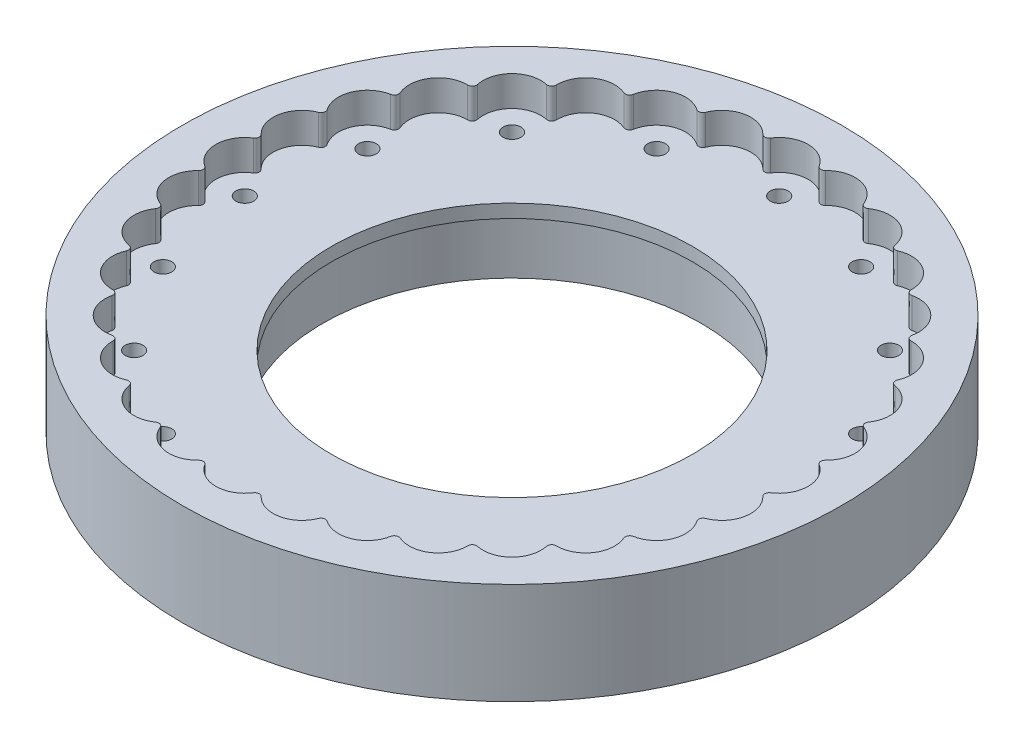
SolidWorks part; units mm, degrees
material "尼龙 101"
ref_plane "前视基准面" through (0, 0, 0) normal (0, 0, 1) x (1, 0, 0)
ref_plane "上视基准面" through (0, 0, 0) normal (0, 1, 0) x (1, 0, 0)
ref_plane "右视基准面" through (0, 0, 0) normal (1, 0, 0) x (0, 0, -1)
sketch "草图1" plane through (0, 0, 0) normal (0, 1, 0) x (1, 0, 0)
  line L0 (-3, 0) -> (-61.8471, 11.7054) construction
  line L1 (-63, 0) -> (-3, 0) construction
  line L2 (-3, 0) -> (-62.7111, 5.881) construction
  line L3 (-61.8471, 11.7054) -> (-80.5752, 15.4307) construction
  line L4 (-63, 0) -> (-84.6703, 0) construction
  arc A23 (51.1029, 1.1255) -> (51, 0) centre (57.2058, 0) ccw construction
  circle A26 centre (-45.4264, 42.4264) radius 6.5 construction
  circle A27 centre (-25.961, 55.4328) radius 6.5 construction
  circle A28 centre (-3, 60) radius 6.5 construction
  circle A29 centre (19.961, 55.4328) radius 6.5 construction
  circle A30 centre (39.4264, 42.4264) radius 6.5 construction
  circle A31 centre (52.4328, 22.961) radius 6.5 construction
  circle A32 centre (57, 0) radius 6.5 construction
  circle A33 centre (52.4328, -22.961) radius 6.5 construction
  circle A34 centre (39.4264, -42.4264) radius 6.5 construction
  circle A35 centre (19.961, -55.4328) radius 6.5 construction
  circle A36 centre (-3, -60) radius 6.5 construction
  circle A37 centre (-25.961, -55.4328) radius 6.5 construction
  circle A38 centre (-45.4264, -42.4264) radius 6.5 construction
  circle A39 centre (-58.4328, -22.961) radius 6.5 construction
  circle A40 centre (-3, 0) radius 74
  circle A42 centre (-3, 0) radius 60 construction
  arc A46 (-68.2222, 12.9735) -> (-65.1785, 6.1241) centre (-61.8471, 11.7054) ccw
  arc A48 (-69.5, 0) -> (-65.1785, 6.1241) centre (-63, 0) cw
  arc A49 (-68.2222, 12.9735) -> (-62.789, 18.1368) centre (-61.8471, 11.7054) cw
  arc A50 (-64.438, 25.4484) -> (-62.789, 18.1368) centre (-58.4328, 22.961) ccw
  arc A51 (-64.438, 25.4484) -> (-58.1019, 29.4526) centre (-58.4328, 22.961) cw
  arc A52 (-58.2927, 36.9454) -> (-58.1019, 29.4526) centre (-52.8882, 33.3342) ccw
  arc A53 (-58.2927, 36.9454) -> (-51.2972, 39.6365) centre (-52.8882, 33.3342) cw
  arc A54 (-50.0226, 47.0226) -> (-51.2972, 39.6365) centre (-45.4264, 42.4264) ccw
  arc A55 (-50.0226, 47.0226) -> (-42.6365, 48.2972) centre (-45.4264, 42.4264) cw
  arc A56 (-39.9454, 55.2927) -> (-42.6365, 48.2972) centre (-36.3342, 49.8882) ccw
  arc A57 (-39.9454, 55.2927) -> (-32.4526, 55.1019) centre (-36.3342, 49.8882) cw
  arc A58 (-28.4484, 61.438) -> (-32.4526, 55.1019) centre (-25.961, 55.4328) ccw
  arc A59 (-28.4484, 61.438) -> (-21.1368, 59.789) centre (-25.961, 55.4328) cw
  arc A60 (-15.9735, 65.2222) -> (-21.1368, 59.789) centre (-14.7054, 58.8471) ccw
  arc A61 (-15.9735, 65.2222) -> (-9.1241, 62.1785) centre (-14.7054, 58.8471) cw
  arc A62 (-3, 66.5) -> (-9.1241, 62.1785) centre (-3, 60) ccw
  arc A63 (-3, 66.5) -> (3.1241, 62.1785) centre (-3, 60) cw
  arc A64 (9.9735, 65.2222) -> (3.1241, 62.1785) centre (8.7054, 58.8471) ccw
  arc A65 (9.9735, 65.2222) -> (15.1368, 59.789) centre (8.7054, 58.8471) cw
  arc A66 (22.4484, 61.438) -> (15.1368, 59.789) centre (19.961, 55.4328) ccw
  arc A67 (22.4484, 61.438) -> (26.4526, 55.1019) centre (19.961, 55.4328) cw
  arc A68 (33.9454, 55.2927) -> (26.4526, 55.1019) centre (30.3342, 49.8882) ccw
  arc A69 (33.9454, 55.2927) -> (36.6365, 48.2972) centre (30.3342, 49.8882) cw
  arc A70 (44.0226, 47.0226) -> (36.6365, 48.2972) centre (39.4264, 42.4264) ccw
  arc A71 (44.0226, 47.0226) -> (45.2972, 39.6365) centre (39.4264, 42.4264) cw
  arc A72 (52.2927, 36.9454) -> (45.2972, 39.6365) centre (46.8882, 33.3342) ccw
  arc A73 (52.2927, 36.9454) -> (52.1019, 29.4526) centre (46.8882, 33.3342) cw
  arc A74 (58.438, 25.4484) -> (52.1019, 29.4526) centre (52.4328, 22.961) ccw
  arc A75 (58.438, 25.4484) -> (56.789, 18.1368) centre (52.4328, 22.961) cw
  arc A76 (62.2222, 12.9735) -> (56.789, 18.1368) centre (55.8471, 11.7054) ccw
  arc A77 (62.2222, 12.9735) -> (59.1785, 6.1241) centre (55.8471, 11.7054) cw
  arc A78 (63.5, 0) -> (59.1785, 6.1241) centre (57, 0) ccw
  arc A79 (63.5, 0) -> (59.1785, -6.1241) centre (57, 0) cw
  arc A80 (62.2222, -12.9735) -> (59.1785, -6.1241) centre (55.8471, -11.7054) ccw
  arc A81 (62.2222, -12.9735) -> (56.789, -18.1368) centre (55.8471, -11.7054) cw
  arc A82 (58.438, -25.4484) -> (56.789, -18.1368) centre (52.4328, -22.961) ccw
  arc A83 (58.438, -25.4484) -> (52.1019, -29.4526) centre (52.4328, -22.961) cw
  arc A84 (52.2927, -36.9454) -> (52.1019, -29.4526) centre (46.8882, -33.3342) ccw
  arc A85 (52.2927, -36.9454) -> (45.2972, -39.6365) centre (46.8882, -33.3342) cw
  arc A86 (44.0226, -47.0226) -> (45.2972, -39.6365) centre (39.4264, -42.4264) ccw
  arc A87 (44.0226, -47.0226) -> (36.6365, -48.2972) centre (39.4264, -42.4264) cw
  arc A88 (33.9454, -55.2927) -> (36.6365, -48.2972) centre (30.3342, -49.8882) ccw
  arc A89 (33.9454, -55.2927) -> (26.4526, -55.1019) centre (30.3342, -49.8882) cw
  arc A90 (22.4484, -61.438) -> (26.4526, -55.1019) centre (19.961, -55.4328) ccw
  arc A91 (22.4484, -61.438) -> (15.1368, -59.789) centre (19.961, -55.4328) cw
  arc A92 (9.9735, -65.2222) -> (15.1368, -59.789) centre (8.7054, -58.8471) ccw
  arc A93 (9.9735, -65.2222) -> (3.1241, -62.1785) centre (8.7054, -58.8471) cw
  arc A94 (-3, -66.5) -> (3.1241, -62.1785) centre (-3, -60) ccw
  arc A95 (-3, -66.5) -> (-9.1241, -62.1785) centre (-3, -60) cw
  arc A96 (-15.9735, -65.2222) -> (-9.1241, -62.1785) centre (-14.7054, -58.8471) ccw
  arc A97 (-15.9735, -65.2222) -> (-21.1368, -59.789) centre (-14.7054, -58.8471) cw
  arc A98 (-28.4484, -61.438) -> (-21.1368, -59.789) centre (-25.961, -55.4328) ccw
  arc A99 (-28.4484, -61.438) -> (-32.4526, -55.1019) centre (-25.961, -55.4328) cw
  arc A100 (-39.9454, -55.2927) -> (-32.4526, -55.1019) centre (-36.3342, -49.8882) ccw
  arc A101 (-39.9454, -55.2927) -> (-42.6365, -48.2972) centre (-36.3342, -49.8882) cw
  arc A102 (-50.0226, -47.0226) -> (-42.6365, -48.2972) centre (-45.4264, -42.4264) ccw
  arc A103 (-50.0226, -47.0226) -> (-51.2972, -39.6365) centre (-45.4264, -42.4264) cw
  arc A104 (-58.2927, -36.9454) -> (-51.2972, -39.6365) centre (-52.8882, -33.3342) ccw
  arc A105 (-58.2927, -36.9454) -> (-58.1019, -29.4526) centre (-52.8882, -33.3342) cw
  arc A106 (-64.438, -25.4484) -> (-58.1019, -29.4526) centre (-58.4328, -22.961) ccw
  arc A107 (-64.438, -25.4484) -> (-62.789, -18.1368) centre (-58.4328, -22.961) cw
  arc A108 (-68.2222, -12.9735) -> (-62.789, -18.1368) centre (-61.8471, -11.7054) ccw
  arc A109 (-68.2222, -12.9735) -> (-65.1785, -6.1241) centre (-61.8471, -11.7054) cw
  arc A110 (-69.5, 0) -> (-65.1785, -6.1241) centre (-63, 0) ccw
  spline S0 degree 4 poles (46.5379, 25.7372) (46.4141, 25.4265) (46.2214, 24.8455) (46.0453, 23.97) (46.0305, 22.7997) (46.2124, 21.7023) (46.5944, 20.6304) (47.1781, 19.6256) (47.8576, 18.8426) (48.5552, 18.26) (49.1821, 17.8581) (49.7006, 17.5881) (50.2292, 17.3676) (50.7615, 17.19) (51.2467, 17.0604) (51.6756, 16.9442) (52.1157, 16.7843) (52.5471, 16.5748) (53.011, 16.2813) (53.5578, 15.8417) (54.0998, 15.2905) (54.8463, 14.3188) (55.4686, 13.069) (55.8643, 11.6469) (55.963, 10.2274) (55.8937, 9.2229) (55.7314, 8.3871) (55.5299, 7.7199) (55.2718, 7.103) (54.9628, 6.5421) (54.6, 6.0376) (54.1839, 5.6019) (53.729, 5.2398) (53.2959, 4.8829) (52.8541, 4.4702) (52.42, 3.9903) (52.024, 3.4526) (51.6787, 2.8581) (51.4223, 2.2845) (51.2601, 1.8044) (51.1585, 1.4093) (51.0974, 1.1068) (51.0631, 0.8925) (51.0397, 0.7088) (51.0244, 0.5571) (51.0146, 0.4347) (51.0053, 0.2754) (51, 0.0893) (50.9991, -0.0325) (51.0033, -0.2118) (51.0104, -0.3723) (51.0237, -0.5582) (51.0467, -0.7767) (51.0935, -1.1015) (51.1814, -1.5223) (51.3208, -2.0042) (51.5289, -2.5363) (51.7967, -3.0719) (52.1288, -3.6024) (52.5013, -4.0845) (52.9041, -4.5182) (53.3092, -4.8924) (53.702, -5.2183) (54.1137, -5.5446) (54.4991, -5.9242) (54.8403, -6.3624) (55.1378, -6.8475) (55.4263, -7.4461) (55.6786, -8.1632) (55.8744, -9.0445) (55.9607, -10.0854) (55.902, -11.1727) (55.6837, -12.2843) (55.3275, -13.3134) (54.856, -14.2458) (54.3439, -14.9904) (53.8416, -15.5634) (53.3534, -16.0123) (52.9029, -16.3539) (52.4611, -16.6202) (52.0385, -16.8165) (51.6463, -16.9514) (51.2956, -17.047) (50.9168, -17.149) (50.5132, -17.271) (50.0892, -17.4238) (49.6494, -17.6158) (49.0833, -17.9121) (48.4035, -18.3646) (47.6718, -19.0234) (46.9704, -19.9376) (46.436, -20.9941) (46.1117, -22.1269) (46.0124, -23.2422) (46.1036, -24.2957) (46.3078, -25.1327) (46.5435, -25.7773) (46.7581, -26.2481) (46.914, -26.5603) (47.0718, -26.8714) (47.2362, -27.2113) (47.3981, -27.6474) (47.5243, -28.1866) (47.5924, -28.7663) (47.6026, -29.4384) (47.5301, -30.1963) (47.3381, -31.083) (46.9787, -32.0726) (46.3109, -33.3348) (45.4042, -34.4509) (44.347, -35.3429) (43.2664, -35.9432) (42.5437, -36.236) (41.8612, -36.4237) (41.3142, -36.5096) (40.8308, -36.531) (40.3614, -36.5031) (39.9223, -36.4373) (39.429, -36.3568) (38.8747, -36.2998) (38.3065, -36.2819) (37.7271, -36.3124) (36.99, -36.4173) (36.0942, -36.6625) (35.1251, -37.109) (34.1566, -37.8104) (33.3468, -38.6733) (32.7332, -39.6305) (32.365, -40.5265) (32.1683, -41.3066) (32.0778, -41.929) (32.0418, -42.3994) (32.0358, -42.8432) (32.0497, -43.2589) (32.0714, -43.6463) (32.0826, -44.0066) (32.0632, -44.417) (31.9953, -44.8732) (31.8342, -45.5014) (31.5334, -46.239) (31.0863, -47.0125) (30.2784, -48.0426) (29.2767, -48.9308) (28.0765, -49.659) (26.7888, -50.1357) (25.7857, -50.3555) (24.9142, -50.4297) (24.1917, -50.4106) (23.5355, -50.3216) (22.9511, -50.1778) (22.4651, -49.9941) (22.0782, -49.7927) (21.7795, -49.6071) (21.5546, -49.4615) (21.2725, -49.2809) (20.928, -49.0738) (20.5013, -48.8474) (19.9846, -48.6223) (19.434, -48.4365) (18.8519, -48.2978) (18.1069, -48.1932) (17.1874, -48.1824) (16.1397, -48.343) (15.0305, -48.7429) (14.036, -49.3297) (13.2407, -50.0153) (12.6167, -50.7563) (12.1857, -51.4457) (11.8991, -52.0281) (11.6878, -52.5417) (11.526, -52.9744) (11.3359, -53.4202) (11.0812, -53.8588) (10.7673, -54.2823) (10.3968, -54.6857) (9.919, -55.118) (9.3192, -55.5548) (8.5533, -55.9873) (7.6098, -56.3665) (6.5728, -56.6314) (5.4562, -56.7578) (4.3706, -56.7287) (3.3372, -56.5582) (2.4735, -56.2932) (1.7785, -55.9874) (1.2003, -55.6539) (0.7315, -55.3183) (0.3297, -54.9579) (-0.0031, -54.5808) (-0.2691, -54.1986) (-0.4996, -53.8375) (-0.799, -53.3974) (-1.189, -52.8945) (-1.7518, -52.3018) (-2.5487, -51.6731) (-3.5127, -51.1471) (-4.6341, -50.7864) (-5.8197, -50.642) (-6.9885, -50.7226) (-8.0385, -50.9971) (-8.9494, -51.4066) (-9.6407, -51.8441) (-10.1588, -52.2535) (-10.5841, -52.6447) (-10.8891, -52.9527) (-11.1549, -53.2129) (-11.4512, -53.4676) (-11.7835, -53.7079) (-12.2085, -53.9529) (-12.7305, -54.1823) (-13.3637, -54.3899) (-14.1104, -54.5474) (-15.0125, -54.6285) (-16.0592, -54.5811) (-17.1309, -54.3847) (-18.204, -54.0281) (-19.1516, -53.5586) (-19.9687, -53.0108) (-20.7121, -52.3651) (-21.2707, -51.7315) (-21.7011, -51.088) (-21.9912, -50.4891) (-22.155, -50.0306) (-22.2585, -49.5926) (-22.3227, -49.1847) (-22.3899, -48.7713) (-22.4739, -48.3546) (-22.6085, -47.8313) (-22.8424, -47.1546) (-23.2318, -46.3575) (-23.8544, -45.4791) (-24.6871, -44.6677) (-25.6692, -44.0188) (-26.6389, -43.6178) (-27.5154, -43.4106) (-28.2524, -43.3323) (-28.8472, -43.3254) (-29.4322, -43.3725) (-30.003, -43.4693) (-30.5614, -43.6126) (-31.0373, -43.7728) (-31.4387, -43.9271) (-31.8427, -44.0792) (-32.2579, -44.2061) (-32.7611, -44.2963) (-33.347, -44.3297) (-34.0225, -44.2957) (-34.7782, -44.1696) (-35.6535, -43.9116) (-36.6179, -43.4757) (-37.7704, -42.7458) (-38.7933, -41.7926) (-39.611, -40.6949) (-40.1395, -39.6116) (-40.3976, -38.8546) (-40.5426, -38.2008) (-40.6112, -37.6643) (-40.6244, -37.1634) (-40.5888, -36.7038) (-40.513, -36.2896) (-40.4169, -35.9209) (-40.2866, -35.4356) (-40.1742, -34.9317) (-40.0977, -34.4072) (-40.055, -33.7098) (-40.0823, -32.9434) (-40.242, -32.0266) (-40.6161, -30.9905) (-41.1976, -29.9862) (-41.9718, -29.089) (-42.813, -28.4312) (-43.6374, -27.9836) (-44.3396, -27.7115) (-44.9036, -27.5499) (-45.4676, -27.4392) (-46.0267, -27.3726) (-46.531, -27.3441) (-46.9786, -27.3217) (-47.4491, -27.2608) (-47.924, -27.1472) (-48.4491, -26.9557) (-49.0877, -26.6351) (-49.7446, -26.2008) (-50.6925, -25.3887) (-51.5674, -24.2757) (-52.2468, -22.9494) (-52.6787, -21.3876) (-52.7938, -20.2381) (-52.7415, -19.2513) (-52.5869, -18.4477) (-52.4194, -17.8829) (-52.2031, -17.3696) (-51.9445, -16.9122) (-51.6489, -16.5156) (-51.3534, -16.1582) (-51.0001, -15.7004) (-50.6155, -15.1236) (-50.215, -14.3486) (-49.8747, -13.3327) (-49.7104, -12.2175) (-49.7626, -11.0381) (-50.0365, -9.8863) (-50.5035, -8.838) (-51.1016, -7.968) (-51.767, -7.2731) (-52.3746, -6.7892) (-52.8873, -6.4554) (-53.352, -6.1961) (-53.7558, -5.9914) (-54.1811, -5.7701) (-54.6019, -5.4873) (-55.0061, -5.1386) (-55.388, -4.7281) (-55.8029, -4.184) (-56.2163, -3.4883) (-56.5934, -2.616) (-56.8794, -1.5636) (-57.0192, -0.4644) (-57.0056, 0.6609) (-56.8431, 1.7289) (-56.5512, 2.7215) (-56.1864, 3.5378) (-55.8005, 4.1844) (-55.4038, 4.7095) (-55.0213, 5.1241) (-54.6067, 5.4849) (-54.1623, 5.7832) (-53.6999, 6.019) (-53.2522, 6.2482) (-52.7801, 6.5213) (-52.2943, 6.8511) (-51.7159, 7.3247) (-51.0958, 7.9792) (-50.5093, 8.8286) (-50.0309, 9.8972) (-49.7598, 11.0441) (-49.7119, 12.2402) (-49.8762, 13.3181) (-50.1782, 14.2422) (-50.5297, 14.9617) (-50.8583, 15.4946) (-51.1503, 15.8971) (-51.3791, 16.1864) (-51.6107, 16.4733) (-51.8529, 16.7821) (-52.1097, 17.1857) (-52.3487, 17.6957) (-52.5356, 18.2511) (-52.6793, 18.8847) (-52.763, 19.5933) (-52.7701, 20.454) (-52.6495, 21.4551) (-52.3771, 22.4981) (-51.9324, 23.5552) (-51.3729, 24.4924) (-50.7281, 25.3031) (-49.9819, 26.0211) (-49.2536, 26.5457) (-48.5459, 26.9194) (-47.9336, 27.1417) (-47.4843, 27.2532) (-47.0763, 27.3113) (-46.7156, 27.3356) (-46.3267, 27.3549) (-45.9101, 27.3865) (-45.4675, 27.4417) (-45.0015, 27.5305) (-44.3901, 27.6912) (-43.6335, 27.9763) (-42.7808, 28.447) (-41.8967, 29.1702) (-41.1366, 30.0712) (-40.5592, 31.0993) (-40.2209, 32.1183) (-40.0728, 33.0677) (-40.0563, 33.8576) (-40.1067, 34.4963) (-40.2075, 35.0962) (-40.3418, 35.6563) (-40.4802, 36.1417) (-40.5678, 36.5674) (-40.6138, 37.0012) (-40.6228, 37.442) (-40.5823, 37.957) (-40.4594, 38.6248) (-40.2357, 39.3609) (-39.8665, 40.1996) (-39.3093, 41.105) (-38.5945, 41.9688) (-37.7193, 42.7584) (-36.7891, 43.3798) (-35.8364, 43.84) (-34.9691, 44.1216) (-34.2184, 44.27) (-33.545, 44.3264) (-32.9584, 44.3148) (-32.4068, 44.2406) (-31.8988, 44.1039) (-31.436, 43.9247) (-30.9987, 43.7594) (-30.449, 43.5789) (-29.7785, 43.4164) (-28.9191, 43.3079) (-27.8569, 43.3383) (-26.757, 43.5667) (-25.6692, 44.0207) (-24.684, 44.6726) (-23.8603, 45.4711) (-23.2924, 46.269) (-22.9216, 46.9921) (-22.6921, 47.5848) (-22.5511, 48.0407) (-22.4467, 48.4768) (-22.3698, 48.8893) (-22.3091, 49.2753) (-22.2491, 49.6326) (-22.1523, 50.0344) (-21.9978, 50.4724) (-21.7764, 50.9361) (-21.482, 51.4161) (-21.0854, 51.9441) (-20.5679, 52.4988) (-19.8818, 53.0808) (-19.0059, 53.6423) (-18.0145, 54.1038) (-16.9178, 54.4377) (-15.8549, 54.6016) (-14.8516, 54.6199) (-13.9999, 54.5266) (-13.3064, 54.3732) (-12.6928, 54.1684) (-12.1604, 53.929) (-11.6778, 53.643) (-11.3015, 53.3503) (-11.0187, 53.0802) (-10.7585, 52.8208) (-10.4964, 52.563) (-10.1304, 52.2302) (-9.6404, 51.8467) (-8.9692, 51.4191) (-8.0913, 51.0165) (-7.0449, 50.7309) (-5.8547, 50.64) (-4.6842, 50.7757) (-3.5637, 51.1281) (-2.6486, 51.6152) (-1.9245, 52.1589) (-1.3864, 52.6821) (-1.0025, 53.1293) (-0.6771, 53.5709) (-0.3982, 53.9941) (-0.1162, 54.4338) (0.2241, 54.8506) (0.6253, 55.2305) (1.0772, 55.5722) (1.6416, 55.9168) (2.3267, 56.2378) (3.1797, 56.5198) (4.2016, 56.7104) (5.2866, 56.7631) (6.4144, 56.66) (7.4766, 56.4105) (8.4562, 56.0346) (9.2521, 55.5984) (9.8752, 55.154) (10.3724, 54.7109) (10.7582, 54.2944) (11.0488, 53.9039) (11.2569, 53.556) (11.4258, 53.2121) (11.5625, 52.8773) (11.7103, 52.4828) (11.9209, 51.9813) (12.1928, 51.4389) (12.5985, 50.7878) (13.1988, 50.0572) (13.9876, 49.3606) (14.9807, 48.7666) (16.0976, 48.3562) (17.2682, 48.1654) (18.3284, 48.1967) (19.244, 48.3746) (19.9605, 48.6113) (20.5094, 48.8503) (21.0146, 49.1208) (21.4217, 49.3736) (21.7644, 49.5994) (22.061, 49.7799) (22.3115, 49.9131) (22.6419, 50.061) (23.0591, 50.2055) (23.561, 50.3258) (24.2389, 50.4157) (25.0178, 50.4296) (25.9392, 50.3338) (26.9809, 50.0765) (28.32, 49.538) (29.5308, 48.7459) (30.5312, 47.7796) (31.2405, 46.7598) (31.6056, 46.0664) (31.8606, 45.4025) (31.9997, 44.8638) (32.0673, 44.3826) (32.0836, 43.9106) (32.0614, 43.4651) (32.0348, 42.9634) (32.0393, 42.4031) (32.0856, 41.8333) (32.182, 41.2578) (32.3713, 40.5332) (32.7195, 39.6672) (33.2739, 38.7585) (34.0745, 37.8856) (35.0067, 37.1899) (35.9971, 36.6968) (36.8947, 36.432) (37.6572, 36.3175) (38.3592, 36.2814) (38.8924, 36.299) (39.4083, 36.3557) (39.9069, 36.4338) (40.2839, 36.4925) (40.7045, 36.5289) (41.1671, 36.5204) (41.6662, 36.4586) (42.1957, 36.337) (42.8347, 36.1271) (43.5651, 35.7931) (44.3633, 35.2983) (45.188, 34.6103) (46.1279, 33.5815) (46.8494, 32.4192) (47.337, 31.1804) (47.5589, 30.0001) (47.6088, 29.2392) (47.5762, 28.5668) (47.4863, 27.9897) (47.349, 27.4996) (47.1843, 27.0997) (46.9931, 26.7142) (46.7974, 26.333) (46.5867, 25.8792) (46.3831, 25.3424) (46.2237, 24.7888) (46.1116, 24.2161) (46.0512, 23.6278) (46.0449, 22.8915) (46.1493, 22.0014) (46.4363, 20.9879) (46.9745, 19.9251) (47.7041, 18.9865) (48.4998, 18.2848) (49.285, 17.7868) (49.9686, 17.4674) (50.5132, 17.2692) (51.0085, 17.1221) (51.4478, 17.0085) (51.912, 16.8692) (52.3842, 16.6623) (52.8554, 16.3864) (53.3182, 16.0422) (53.7955, 15.609) (54.2709, 15.0778) (54.7703, 14.3808) (55.2461, 13.4987) (55.6279, 12.4872) (55.8786, 11.3552) (55.9619, 10.2497) (55.8955, 9.1942) (55.7154, 8.2993) (55.4758, 7.57) (55.1961, 6.9567) (54.9032, 6.4546) (54.5797, 6.0202) (54.2341, 5.6566) (53.8813, 5.3592) (53.5523, 5.0956) (53.2287, 4.8192) (52.9161, 4.5249) (52.5434, 4.1311) (52.1808, 3.6766) (51.8445, 3.1605) (51.579, 2.6398) (51.4091, 2.232) (51.2991, 1.9115) (51.2333, 1.6918) (51.1844, 1.5058) (51.1465, 1.3427) (51.1136, 1.185) (51.0924, 1.0702) (51.0671, 0.9132) (51.0452, 0.7545) (51.0245, 0.5678) (51.0076, 0.3469) (50.9975, 0.0834) (51.0008, -0.2155) (51.0227, -0.5894) (51.078, -1.035) (51.1839, -1.5486) (51.4036, -2.2603) (51.7236, -2.9659) (52.1483, -3.6478) (52.6384, -4.2427) (53.0557, -4.6645) (53.4116, -4.9778) (53.6865, -5.203) (53.9622, -5.4272) (54.1981, -5.6295) (54.4282, -5.8597) (54.6955, -6.1751) (54.9531, -6.5374) (55.213, -6.9884) (55.4926, -7.613) (55.7287, -8.3512) (55.9038, -9.2579) (55.962, -10.3279) (55.8389, -11.7595) (55.3724, -13.3703) (54.624, -14.7129) (53.6976, -15.737) (52.9621, -16.3159) (52.4954, -16.6036) (52.0618, -16.8071) (51.6202, -16.9607) (51.191, -17.0744) (50.7066, -17.2066) (50.1754, -17.3878) (49.6487, -17.6127) (49.1328, -17.887) (48.5098, -18.2942) (47.8181, -18.8824) (47.1451, -19.672) (46.5697, -20.6837) (46.1967, -21.7626) (46.0167, -22.923) (46.0486, -23.8183) (46.1486, -24.4241) (46.2252, -24.7497) knots 0 0 0 0 0 0.002873 0.005251 0.007629 0.010007 0.012383 0.014979 0.017557 0.018862 0.020166 0.02137 0.022574 0.023779 0.024983 0.025687 0.026391 0.027799 0.029095 0.030392 0.032409 0.034427 0.039593 0.04229 0.044987 0.046603 0.04822 0.049593 0.050967 0.05234 0.053712 0.054918 0.056125 0.057331 0.058537 0.060108 0.061678 0.063057 0.064435 0.065497 0.066028 0.066559 0.06709 0.067355 0.067621 0.067886 0.068152 0.068683 0.069002 0.069321 0.06964 0.069959 0.070597 0.071235 0.072446 0.073657 0.074899 0.076141 0.077584 0.079028 0.080125 0.081222 0.082319 0.083415 0.084637 0.085858 0.087078 0.088298 0.090338 0.092377 0.094812 0.097246 0.099663 0.10208 0.104139 0.106198 0.107406 0.108614 0.109832 0.111049 0.11183 0.112611 0.113392 0.114172 0.115202 0.116232 0.117262 0.118292 0.120689 0.123232 0.125678 0.128137 0.130806 0.133296 0.135241 0.137186 0.138186 0.139185 0.139685 0.140185 0.141184 0.142428 0.143672 0.144932 0.146191 0.148196 0.150201 0.152706 0.155211 0.160423 0.162457 0.164492 0.1658 0.167108 0.168529 0.169239 0.169949 0.171145 0.172341 0.173537 0.174732 0.176026 0.17732 0.179927 0.182686 0.185136 0.187531 0.190041 0.192403 0.193415 0.194428 0.195441 0.196454 0.197228 0.198002 0.198776 0.19955 0.200754 0.201958 0.204338 0.206371 0.208404 0.213175 0.21576 0.218345 0.220159 0.221973 0.223259 0.224544 0.225839 0.227134 0.22771 0.228286 0.228861 0.229437 0.230589 0.23174 0.233008 0.234276 0.235576 0.236876 0.239463 0.24215 0.244626 0.246945 0.249334 0.251127 0.25292 0.253913 0.254906 0.255899 0.256891 0.258072 0.259252 0.260421 0.26159 0.263602 0.265615 0.267959 0.270303 0.272772 0.275241 0.277259 0.279276 0.280514 0.281752 0.282987 0.284221 0.285142 0.286063 0.286984 0.287905 0.289715 0.291526 0.293988 0.296594 0.299097 0.301588 0.304193 0.306602 0.30837 0.310139 0.311204 0.312269 0.313333 0.313866 0.314398 0.315625 0.316852 0.318071 0.31929 0.321343 0.323396 0.325831 0.328267 0.330675 0.333082 0.33489 0.336697 0.339117 0.340317 0.341518 0.342405 0.343292 0.344179 0.345066 0.346004 0.346943 0.34882 0.351209 0.353598 0.356148 0.358755 0.361262 0.362562 0.363862 0.365114 0.366367 0.367599 0.368831 0.370063 0.370679 0.371295 0.372541 0.373788 0.375058 0.376329 0.378343 0.380357 0.382876 0.385394 0.390023 0.392288 0.394554 0.395716 0.396878 0.398037 0.399195 0.400014 0.400832 0.40165 0.402469 0.404333 0.405265 0.406198 0.408469 0.410909 0.413223 0.415614 0.418392 0.421029 0.422338 0.423647 0.424855 0.426064 0.427272 0.428481 0.429197 0.429913 0.431345 0.432667 0.433988 0.436042 0.438096 0.443359 0.446048 0.448738 0.451962 0.453234 0.454505 0.45576 0.457015 0.458011 0.459008 0.460004 0.461001 0.462979 0.464957 0.467475 0.470169 0.472606 0.475041 0.477593 0.479975 0.481628 0.48328 0.484253 0.485226 0.486199 0.487172 0.488371 0.489571 0.490776 0.491982 0.494244 0.496506 0.498914 0.501323 0.503735 0.506146 0.508167 0.510188 0.511396 0.512603 0.513815 0.515027 0.516108 0.517189 0.51827 0.519352 0.520791 0.52223 0.524684 0.527074 0.529614 0.532236 0.534748 0.537299 0.538929 0.540559 0.541615 0.542671 0.5432 0.543728 0.544784 0.546042 0.547299 0.548555 0.549811 0.551616 0.55342 0.555935 0.55845 0.560847 0.563243 0.565285 0.567326 0.569719 0.570928 0.572137 0.572913 0.573689 0.574466 0.575242 0.57626 0.577279 0.578297 0.579315 0.581688 0.58421 0.586622 0.589075 0.591763 0.59428 0.595792 0.597303 0.59854 0.599777 0.601014 0.602251 0.602878 0.603505 0.604759 0.606034 0.607308 0.609332 0.611355 0.613885 0.616415 0.618932 0.62145 0.623464 0.625478 0.626745 0.628012 0.629262 0.630511 0.631516 0.63252 0.633525 0.634529 0.636485 0.63844 0.640943 0.643622 0.646079 0.648508 0.65104 0.653425 0.654449 0.655473 0.656498 0.657522 0.6583 0.659078 0.659856 0.660634 0.661848 0.663061 0.664263 0.665465 0.667516 0.669566 0.671973 0.674379 0.676883 0.679386 0.681182 0.682977 0.684228 0.685479 0.686732 0.687985 0.689038 0.689564 0.690091 0.691143 0.692196 0.693813 0.69543 0.697969 0.700465 0.703081 0.705626 0.708032 0.710501 0.711942 0.713382 0.714471 0.715561 0.71665 0.71774 0.718956 0.720172 0.721386 0.7226 0.72463 0.72666 0.729084 0.731507 0.733934 0.736361 0.738429 0.740496 0.74171 0.742923 0.744145 0.745367 0.745884 0.746401 0.747436 0.748471 0.749506 0.751074 0.752643 0.755051 0.757604 0.760067 0.76253 0.765219 0.767733 0.769126 0.770518 0.771694 0.77287 0.774046 0.774634 0.775222 0.775853 0.776483 0.777743 0.779011 0.780279 0.78235 0.784422 0.786946 0.789471 0.794708 0.796752 0.798796 0.800112 0.801427 0.802853 0.803566 0.804278 0.805481 0.806683 0.807885 0.809088 0.810389 0.811691 0.814312 0.817081 0.819476 0.821805 0.824257 0.826538 0.827478 0.828417 0.830295 0.831114 0.831934 0.832754 0.833574 0.834738 0.835902 0.837068 0.838235 0.840511 0.842786 0.845111 0.847435 0.852449 0.854454 0.85646 0.857724 0.858988 0.860229 0.86147 0.862084 0.862698 0.863926 0.865154 0.866381 0.867626 0.868871 0.870163 0.871456 0.873945 0.876546 0.879162 0.881628 0.884101 0.885613 0.887126 0.888101 0.889076 0.890051 0.891027 0.89226 0.893494 0.894734 0.895974 0.897792 0.899609 0.902086 0.904563 0.90705 0.909538 0.91158 0.913622 0.914871 0.916121 0.917365 0.918608 0.919515 0.920421 0.921327 0.922233 0.92317 0.924108 0.925983 0.92722 0.928456 0.92912 0.929784 0.930116 0.930449 0.930781 0.931113 0.931435 0.931756 0.932078 0.9324 0.933043 0.933686 0.934329 0.934972 0.936259 0.937543 0.938828 0.941365 0.942893 0.944422 0.94544 0.946458 0.946967 0.947476 0.948494 0.949127 0.94976 0.951026 0.952309 0.953592 0.955632 0.957672 0.960221 0.962771 0.967934 0.971965 0.973261 0.974557 0.975962 0.976665 0.977367 0.978572 0.979776 0.980981 0.982185 0.983488 0.984791 0.987368 0.989961 0.992349 0.994736 0.997126 1 1 1 1 1 construction
  spline S1 degree 4 poles (51, 0) (51, -0.032) (51.0006, -0.0965) (51.0033, -0.2118) (51.0104, -0.3723) (51.0237, -0.5582) (51.0467, -0.7767) (51.0935, -1.1015) (51.1814, -1.5223) (51.3208, -2.0042) (51.5289, -2.5363) (51.7967, -3.0719) (52.1288, -3.6024) (52.5013, -4.0845) (52.9041, -4.5182) (53.3092, -4.8924) (53.702, -5.2183) (54.1137, -5.5446) (54.4991, -5.9242) (54.8403, -6.3624) (55.1378, -6.8475) (55.4263, -7.4461) (55.6786, -8.1632) (55.8744, -9.0445) (55.9607, -10.0854) (55.902, -11.1727) (55.6837, -12.2843) (55.3275, -13.3134) (54.856, -14.2458) (54.3439, -14.9904) (53.8416, -15.5634) (53.3534, -16.0123) (52.9029, -16.3539) (52.4611, -16.6202) (52.0385, -16.8165) (51.6463, -16.9514) (51.2956, -17.047) (50.9168, -17.149) (50.5132, -17.271) (50.0892, -17.4238) (49.6494, -17.6158) (49.0833, -17.9121) (48.4035, -18.3646) (47.6718, -19.0234) (46.9704, -19.9376) (46.436, -20.9941) (46.1117, -22.1269) (46.0124, -23.2422) (46.1036, -24.2957) (46.3078, -25.1327) (46.5435, -25.7773) (46.7581, -26.2481) (46.914, -26.5603) (47.0718, -26.8714) (47.2362, -27.2113) (47.3981, -27.6474) (47.5243, -28.1866) (47.5924, -28.7663) (47.6026, -29.4384) (47.5301, -30.1963) (47.3381, -31.083) (46.9787, -32.0726) (46.3109, -33.3348) (45.4042, -34.4509) (44.347, -35.3429) (43.2664, -35.9432) (42.5437, -36.236) (41.8612, -36.4237) (41.3142, -36.5096) (40.8308, -36.531) (40.3614, -36.5031) (39.9223, -36.4373) (39.429, -36.3568) (38.8747, -36.2998) (38.3065, -36.2819) (37.7271, -36.3124) (36.99, -36.4173) (36.0942, -36.6625) (35.1251, -37.109) (34.1566, -37.8104) (33.3468, -38.6733) (32.7332, -39.6305) (32.365, -40.5265) (32.1683, -41.3066) (32.0778, -41.929) (32.0418, -42.3994) (32.0358, -42.8432) (32.0497, -43.2589) (32.0714, -43.6463) (32.0826, -44.0066) (32.0632, -44.417) (31.9953, -44.8732) (31.8342, -45.5014) (31.5334, -46.239) (31.0863, -47.0125) (30.2784, -48.0426) (29.2767, -48.9308) (28.0765, -49.659) (26.7888, -50.1357) (25.7857, -50.3555) (24.9142, -50.4297) (24.1917, -50.4106) (23.5355, -50.3216) (22.9511, -50.1778) (22.4651, -49.9941) (22.0782, -49.7927) (21.7795, -49.6071) (21.5546, -49.4615) (21.2725, -49.2809) (20.928, -49.0738) (20.5013, -48.8474) (19.9846, -48.6223) (19.434, -48.4365) (18.8519, -48.2978) (18.1069, -48.1932) (17.1874, -48.1824) (16.1397, -48.343) (15.0305, -48.7429) (14.036, -49.3297) (13.2407, -50.0153) (12.6167, -50.7563) (12.1857, -51.4457) (11.8991, -52.0281) (11.6878, -52.5417) (11.526, -52.9744) (11.3359, -53.4202) (11.0812, -53.8588) (10.7673, -54.2823) (10.3968, -54.6857) (9.919, -55.118) (9.3192, -55.5548) (8.5533, -55.9873) (7.6098, -56.3665) (6.5728, -56.6314) (5.4562, -56.7578) (4.3706, -56.7287) (3.3372, -56.5582) (2.4735, -56.2932) (1.7785, -55.9874) (1.2003, -55.6539) (0.7315, -55.3183) (0.3297, -54.9579) (-0.0031, -54.5808) (-0.2691, -54.1986) (-0.4996, -53.8375) (-0.799, -53.3974) (-1.189, -52.8945) (-1.7518, -52.3018) (-2.5487, -51.6731) (-3.5127, -51.1471) (-4.6341, -50.7864) (-5.8197, -50.642) (-6.9885, -50.7226) (-8.0385, -50.9971) (-8.9494, -51.4066) (-9.6407, -51.8441) (-10.1588, -52.2535) (-10.5841, -52.6447) (-10.8891, -52.9527) (-11.1549, -53.2129) (-11.4512, -53.4676) (-11.7835, -53.7079) (-12.2085, -53.9529) (-12.7305, -54.1823) (-13.3637, -54.3899) (-14.1104, -54.5474) (-15.0125, -54.6285) (-16.0592, -54.5811) (-17.1309, -54.3847) (-18.204, -54.0281) (-19.1516, -53.5586) (-19.9687, -53.0108) (-20.7121, -52.3651) (-21.2707, -51.7315) (-21.7011, -51.088) (-21.9912, -50.4891) (-22.155, -50.0306) (-22.2585, -49.5926) (-22.3227, -49.1847) (-22.3899, -48.7713) (-22.4739, -48.3546) (-22.6085, -47.8313) (-22.8424, -47.1546) (-23.2318, -46.3575) (-23.8544, -45.4791) (-24.6871, -44.6677) (-25.6692, -44.0188) (-26.6389, -43.6178) (-27.5154, -43.4106) (-28.2524, -43.3323) (-28.8472, -43.3254) (-29.4322, -43.3725) (-30.003, -43.4693) (-30.5614, -43.6126) (-31.0373, -43.7728) (-31.4387, -43.9271) (-31.8427, -44.0792) (-32.2579, -44.2061) (-32.7611, -44.2963) (-33.347, -44.3297) (-34.0225, -44.2957) (-34.7782, -44.1696) (-35.6535, -43.9116) (-36.6179, -43.4757) (-37.7704, -42.7458) (-38.7933, -41.7926) (-39.611, -40.6949) (-40.1395, -39.6116) (-40.3976, -38.8546) (-40.5426, -38.2008) (-40.6112, -37.6643) (-40.6244, -37.1634) (-40.5888, -36.7038) (-40.513, -36.2896) (-40.4169, -35.9209) (-40.2866, -35.4356) (-40.1742, -34.9317) (-40.0977, -34.4072) (-40.055, -33.7098) (-40.0823, -32.9434) (-40.242, -32.0266) (-40.6161, -30.9905) (-41.1976, -29.9862) (-41.9718, -29.089) (-42.813, -28.4312) (-43.6374, -27.9836) (-44.3396, -27.7115) (-44.9036, -27.5499) (-45.4676, -27.4392) (-46.0267, -27.3726) (-46.531, -27.3441) (-46.9786, -27.3217) (-47.4491, -27.2608) (-47.924, -27.1472) (-48.4491, -26.9557) (-49.0877, -26.6351) (-49.7446, -26.2008) (-50.6925, -25.3887) (-51.5674, -24.2757) (-52.2468, -22.9494) (-52.6787, -21.3876) (-52.7938, -20.2381) (-52.7415, -19.2513) (-52.5869, -18.4477) (-52.4194, -17.8829) (-52.2031, -17.3696) (-51.9445, -16.9122) (-51.6489, -16.5156) (-51.3534, -16.1582) (-51.0001, -15.7004) (-50.6155, -15.1236) (-50.215, -14.3486) (-49.8747, -13.3327) (-49.7104, -12.2175) (-49.7626, -11.0381) (-50.0365, -9.8863) (-50.5035, -8.838) (-51.1016, -7.968) (-51.767, -7.2731) (-52.3746, -6.7892) (-52.8873, -6.4554) (-53.352, -6.1961) (-53.7558, -5.9914) (-54.1811, -5.7701) (-54.6019, -5.4873) (-55.0061, -5.1386) (-55.388, -4.7281) (-55.8029, -4.184) (-56.2163, -3.4883) (-56.5934, -2.616) (-56.8794, -1.5636) (-57.0192, -0.4644) (-57.0056, 0.6609) (-56.8431, 1.7289) (-56.5512, 2.7215) (-56.1864, 3.5378) (-55.8005, 4.1844) (-55.4038, 4.7095) (-55.0213, 5.1241) (-54.6067, 5.4849) (-54.1623, 5.7832) (-53.6999, 6.019) (-53.2522, 6.2482) (-52.7801, 6.5213) (-52.2943, 6.8511) (-51.7159, 7.3247) (-51.0958, 7.9792) (-50.5093, 8.8286) (-50.0309, 9.8972) (-49.7598, 11.0441) (-49.7119, 12.2402) (-49.8762, 13.3181) (-50.1782, 14.2422) (-50.5297, 14.9617) (-50.8583, 15.4946) (-51.1503, 15.8971) (-51.3791, 16.1864) (-51.6107, 16.4733) (-51.8529, 16.7821) (-52.1097, 17.1857) (-52.3487, 17.6957) (-52.5356, 18.2511) (-52.6793, 18.8847) (-52.763, 19.5933) (-52.7701, 20.454) (-52.6495, 21.4551) (-52.3771, 22.4981) (-51.9324, 23.5552) (-51.3729, 24.4924) (-50.7281, 25.3031) (-49.9819, 26.0211) (-49.2536, 26.5457) (-48.5459, 26.9194) (-47.9336, 27.1417) (-47.4843, 27.2532) (-47.0763, 27.3113) (-46.7156, 27.3356) (-46.3267, 27.3549) (-45.9101, 27.3865) (-45.4675, 27.4417) (-45.0015, 27.5305) (-44.3901, 27.6912) (-43.6335, 27.9763) (-42.7808, 28.447) (-41.8967, 29.1702) (-41.1366, 30.0712) (-40.5592, 31.0993) (-40.2209, 32.1183) (-40.0728, 33.0677) (-40.0563, 33.8576) (-40.1067, 34.4963) (-40.2075, 35.0962) (-40.3418, 35.6563) (-40.4802, 36.1417) (-40.5678, 36.5674) (-40.6138, 37.0012) (-40.6228, 37.442) (-40.5823, 37.957) (-40.4594, 38.6248) (-40.2357, 39.3609) (-39.8665, 40.1996) (-39.3093, 41.105) (-38.5945, 41.9688) (-37.7193, 42.7584) (-36.7891, 43.3798) (-35.8364, 43.84) (-34.9691, 44.1216) (-34.2184, 44.27) (-33.545, 44.3264) (-32.9584, 44.3148) (-32.4068, 44.2406) (-31.8988, 44.1039) (-31.436, 43.9247) (-30.9987, 43.7594) (-30.449, 43.5789) (-29.7785, 43.4164) (-28.9191, 43.3079) (-27.8569, 43.3383) (-26.757, 43.5667) (-25.6692, 44.0207) (-24.684, 44.6726) (-23.8603, 45.4711) (-23.2924, 46.269) (-22.9216, 46.9921) (-22.6921, 47.5848) (-22.5511, 48.0407) (-22.4467, 48.4768) (-22.3698, 48.8893) (-22.3091, 49.2753) (-22.2491, 49.6326) (-22.1523, 50.0344) (-21.9978, 50.4724) (-21.7764, 50.9361) (-21.482, 51.4161) (-21.0854, 51.9441) (-20.5679, 52.4988) (-19.8818, 53.0808) (-19.0059, 53.6423) (-18.0145, 54.1038) (-16.9178, 54.4377) (-15.8549, 54.6016) (-14.8516, 54.6199) (-13.9999, 54.5266) (-13.3064, 54.3732) (-12.6928, 54.1684) (-12.1604, 53.929) (-11.6778, 53.643) (-11.3015, 53.3503) (-11.0187, 53.0802) (-10.7585, 52.8208) (-10.4964, 52.563) (-10.1304, 52.2302) (-9.6404, 51.8467) (-8.9692, 51.4191) (-8.0913, 51.0165) (-7.0449, 50.7309) (-5.8547, 50.64) (-4.6842, 50.7757) (-3.5637, 51.1281) (-2.6486, 51.6152) (-1.9245, 52.1589) (-1.3864, 52.6821) (-1.0025, 53.1293) (-0.6771, 53.5709) (-0.3982, 53.9941) (-0.1162, 54.4338) (0.2241, 54.8506) (0.6253, 55.2305) (1.0772, 55.5722) (1.6416, 55.9168) (2.3267, 56.2378) (3.1797, 56.5198) (4.2016, 56.7104) (5.2866, 56.7631) (6.4144, 56.66) (7.4766, 56.4105) (8.4562, 56.0346) (9.2521, 55.5984) (9.8752, 55.154) (10.3724, 54.7109) (10.7582, 54.2944) (11.0488, 53.9039) (11.2569, 53.556) (11.4258, 53.2121) (11.5625, 52.8773) (11.7103, 52.4828) (11.9209, 51.9813) (12.1928, 51.4389) (12.5985, 50.7878) (13.1988, 50.0572) (13.9876, 49.3606) (14.9807, 48.7666) (16.0976, 48.3562) (17.2682, 48.1654) (18.3284, 48.1967) (19.244, 48.3746) (19.9605, 48.6113) (20.5094, 48.8503) (21.0146, 49.1208) (21.4217, 49.3736) (21.7644, 49.5994) (22.061, 49.7799) (22.3115, 49.9131) (22.6419, 50.061) (23.0591, 50.2055) (23.561, 50.3258) (24.2389, 50.4157) (25.0178, 50.4296) (25.9392, 50.3338) (26.9809, 50.0765) (28.32, 49.538) (29.5308, 48.7459) (30.5312, 47.7796) (31.2405, 46.7598) (31.6056, 46.0664) (31.8606, 45.4025) (31.9997, 44.8638) (32.0673, 44.3826) (32.0836, 43.9106) (32.0614, 43.4651) (32.0348, 42.9634) (32.0393, 42.4031) (32.0856, 41.8333) (32.182, 41.2578) (32.3713, 40.5332) (32.7195, 39.6672) (33.2739, 38.7585) (34.0745, 37.8856) (35.0067, 37.1899) (35.9971, 36.6968) (36.8947, 36.432) (37.6572, 36.3175) (38.3592, 36.2814) (38.8924, 36.299) (39.4083, 36.3557) (39.9069, 36.4338) (40.2839, 36.4925) (40.7045, 36.5289) (41.1671, 36.5204) (41.6662, 36.4586) (42.1957, 36.337) (42.8347, 36.1271) (43.5651, 35.7931) (44.3633, 35.2983) (45.188, 34.6103) (46.1279, 33.5815) (46.8494, 32.4192) (47.337, 31.1804) (47.5589, 30.0001) (47.6088, 29.2392) (47.5762, 28.5668) (47.4863, 27.9897) (47.349, 27.4996) (47.1843, 27.0997) (46.9931, 26.7142) (46.7974, 26.333) (46.5867, 25.8792) (46.3831, 25.3424) (46.2237, 24.7888) (46.1116, 24.2161) (46.0512, 23.6278) (46.0449, 22.8915) (46.1493, 22.0014) (46.4363, 20.9879) (46.9745, 19.9251) (47.7041, 18.9865) (48.4998, 18.2848) (49.285, 17.7868) (49.9686, 17.4674) (50.5132, 17.2692) (51.0085, 17.1221) (51.4478, 17.0085) (51.912, 16.8692) (52.3842, 16.6623) (52.8554, 16.3864) (53.3182, 16.0422) (53.7955, 15.609) (54.2709, 15.0778) (54.7703, 14.3808) (55.2461, 13.4987) (55.6279, 12.4872) (55.8786, 11.3552) (55.9619, 10.2497) (55.8955, 9.1942) (55.7154, 8.2993) (55.4758, 7.57) (55.1961, 6.9567) (54.9032, 6.4546) (54.5797, 6.0202) (54.2341, 5.6566) (53.8813, 5.3592) (53.5523, 5.0956) (53.2287, 4.8192) (52.9161, 4.5249) (52.5434, 4.1311) (52.1808, 3.6766) (51.8445, 3.1605) (51.579, 2.6398) (51.4091, 2.232) (51.2991, 1.9115) (51.2333, 1.6918) (51.1844, 1.5058) (51.1465, 1.3427) (51.1216, 1.2235) (51.109, 1.1583) (51.1029, 1.1255) knots 0.068683 0.068683 0.068683 0.068683 0.068683 0.069002 0.069321 0.06964 0.069959 0.070597 0.071235 0.072446 0.073657 0.074899 0.076141 0.077584 0.079028 0.080125 0.081222 0.082319 0.083415 0.084637 0.085858 0.087078 0.088298 0.090338 0.092377 0.094812 0.097246 0.099663 0.10208 0.104139 0.106198 0.107406 0.108614 0.109832 0.111049 0.11183 0.112611 0.113392 0.114172 0.115202 0.116232 0.117262 0.118292 0.120689 0.123232 0.125678 0.128137 0.130806 0.133296 0.135241 0.137186 0.138186 0.139185 0.139685 0.140185 0.141184 0.142428 0.143672 0.144932 0.146191 0.148196 0.150201 0.152706 0.155211 0.160423 0.162457 0.164492 0.1658 0.167108 0.168529 0.169239 0.169949 0.171145 0.172341 0.173537 0.174732 0.176026 0.17732 0.179927 0.182686 0.185136 0.187531 0.190041 0.192403 0.193415 0.194428 0.195441 0.196454 0.197228 0.198002 0.198776 0.19955 0.200754 0.201958 0.204338 0.206371 0.208404 0.213175 0.21576 0.218345 0.220159 0.221973 0.223259 0.224544 0.225839 0.227134 0.22771 0.228286 0.228861 0.229437 0.230589 0.23174 0.233008 0.234276 0.235576 0.236876 0.239463 0.24215 0.244626 0.246945 0.249334 0.251127 0.25292 0.253913 0.254906 0.255899 0.256891 0.258072 0.259252 0.260421 0.26159 0.263602 0.265615 0.267959 0.270303 0.272772 0.275241 0.277259 0.279276 0.280514 0.281752 0.282987 0.284221 0.285142 0.286063 0.286984 0.287905 0.289715 0.291526 0.293988 0.296594 0.299097 0.301588 0.304193 0.306602 0.30837 0.310139 0.311204 0.312269 0.313333 0.313866 0.314398 0.315625 0.316852 0.318071 0.31929 0.321343 0.323396 0.325831 0.328267 0.330675 0.333082 0.33489 0.336697 0.339117 0.340317 0.341518 0.342405 0.343292 0.344179 0.345066 0.346004 0.346943 0.34882 0.351209 0.353598 0.356148 0.358755 0.361262 0.362562 0.363862 0.365114 0.366367 0.367599 0.368831 0.370063 0.370679 0.371295 0.372541 0.373788 0.375058 0.376329 0.378343 0.380357 0.382876 0.385394 0.390023 0.392288 0.394554 0.395716 0.396878 0.398037 0.399195 0.400014 0.400832 0.40165 0.402469 0.404333 0.405265 0.406198 0.408469 0.410909 0.413223 0.415614 0.418392 0.421029 0.422338 0.423647 0.424855 0.426064 0.427272 0.428481 0.429197 0.429913 0.431345 0.432667 0.433988 0.436042 0.438096 0.443359 0.446048 0.448738 0.451962 0.453234 0.454505 0.45576 0.457015 0.458011 0.459008 0.460004 0.461001 0.462979 0.464957 0.467475 0.470169 0.472606 0.475041 0.477593 0.479975 0.481628 0.48328 0.484253 0.485226 0.486199 0.487172 0.488371 0.489571 0.490776 0.491982 0.494244 0.496506 0.498914 0.501323 0.503735 0.506146 0.508167 0.510188 0.511396 0.512603 0.513815 0.515027 0.516108 0.517189 0.51827 0.519352 0.520791 0.52223 0.524684 0.527074 0.529614 0.532236 0.534748 0.537299 0.538929 0.540559 0.541615 0.542671 0.5432 0.543728 0.544784 0.546042 0.547299 0.548555 0.549811 0.551616 0.55342 0.555935 0.55845 0.560847 0.563243 0.565285 0.567326 0.569719 0.570928 0.572137 0.572913 0.573689 0.574466 0.575242 0.57626 0.577279 0.578297 0.579315 0.581688 0.58421 0.586622 0.589075 0.591763 0.59428 0.595792 0.597303 0.59854 0.599777 0.601014 0.602251 0.602878 0.603505 0.604759 0.606034 0.607308 0.609332 0.611355 0.613885 0.616415 0.618932 0.62145 0.623464 0.625478 0.626745 0.628012 0.629262 0.630511 0.631516 0.63252 0.633525 0.634529 0.636485 0.63844 0.640943 0.643622 0.646079 0.648508 0.65104 0.653425 0.654449 0.655473 0.656498 0.657522 0.6583 0.659078 0.659856 0.660634 0.661848 0.663061 0.664263 0.665465 0.667516 0.669566 0.671973 0.674379 0.676883 0.679386 0.681182 0.682977 0.684228 0.685479 0.686732 0.687985 0.689038 0.689564 0.690091 0.691143 0.692196 0.693813 0.69543 0.697969 0.700465 0.703081 0.705626 0.708032 0.710501 0.711942 0.713382 0.714471 0.715561 0.71665 0.71774 0.718956 0.720172 0.721386 0.7226 0.72463 0.72666 0.729084 0.731507 0.733934 0.736361 0.738429 0.740496 0.74171 0.742923 0.744145 0.745367 0.745884 0.746401 0.747436 0.748471 0.749506 0.751074 0.752643 0.755051 0.757604 0.760067 0.76253 0.765219 0.767733 0.769126 0.770518 0.771694 0.77287 0.774046 0.774634 0.775222 0.775853 0.776483 0.777743 0.779011 0.780279 0.78235 0.784422 0.786946 0.789471 0.794708 0.796752 0.798796 0.800112 0.801427 0.802853 0.803566 0.804278 0.805481 0.806683 0.807885 0.809088 0.810389 0.811691 0.814312 0.817081 0.819476 0.821805 0.824257 0.826538 0.827478 0.828417 0.830295 0.831114 0.831934 0.832754 0.833574 0.834738 0.835902 0.837068 0.838235 0.840511 0.842786 0.845111 0.847435 0.852449 0.854454 0.85646 0.857724 0.858988 0.860229 0.86147 0.862084 0.862698 0.863926 0.865154 0.866381 0.867626 0.868871 0.870163 0.871456 0.873945 0.876546 0.879162 0.881628 0.884101 0.885613 0.887126 0.888101 0.889076 0.890051 0.891027 0.89226 0.893494 0.894734 0.895974 0.897792 0.899609 0.902086 0.904563 0.90705 0.909538 0.91158 0.913622 0.914871 0.916121 0.917365 0.918608 0.919515 0.920421 0.921327 0.922233 0.92317 0.924108 0.925983 0.92722 0.928456 0.92912 0.929784 0.930116 0.930449 0.930781 0.931113 0.931113 0.931113 0.931113 0.931113 construction
  point P10 (-3, 0)
  dimension "D2" = 63
  dimension "D9" = 11.25
  dimension "D11" = 13
  dimension "D6" = 148
  dimension "D3" = 3
  dimension "D4" = 60
  dimension "D5" = 60
extrude "凸台-拉伸1" add sketch "草图1" along normal blind 6.8
sketch "草图2" plane through (0, 0, 0) normal (0, -1, 0) x (1, 0, 0)
  circle A1 centre (-3, 0) radius 74
  circle A2 centre (-3, 0) radius 74
  dimension "D1" = 0
extrude "凸台-拉伸2" add sketch "草图2" along normal blind 16
sketch "草图3" plane through (0, 0, 0) normal (0, 1, 0) x (1, 0, 0)
  arc A0 (-65.1785, 6.1241) -> (-65.1785, -6.1241) centre (-63, 0) ccw construction
  arc A1 (-65.1785, 6.1241) -> (-65.1785, -6.1241) centre (-63, 0) ccw construction
  circle A2 centre (-63, 0) radius 2
  circle A3 centre (-58.4328, 22.961) radius 2
  circle A4 centre (-45.4264, 42.4264) radius 2
  circle A5 centre (-25.961, 55.4328) radius 2
  circle A6 centre (-3, 60) radius 2
  circle A7 centre (19.961, 55.4328) radius 2
  circle A8 centre (39.4264, 42.4264) radius 2
  circle A9 centre (52.4328, 22.961) radius 2
  circle A10 centre (57, 0) radius 2
  circle A11 centre (52.4328, -22.961) radius 2
  circle A12 centre (39.4264, -42.4264) radius 2
  circle A13 centre (19.961, -55.4328) radius 2
  circle A14 centre (-3, -60) radius 2
  circle A15 centre (-25.961, -55.4328) radius 2
  circle A16 centre (-45.4264, -42.4264) radius 2
  circle A17 centre (-58.4328, -22.961) radius 2
  point P4 (-3, 0)
  dimension "D1" = 4
  dimension "D2" = 3
  dimension "D3" = 60
  dimension "D4" = 60
extrude "切除-拉伸1" cut sketch "草图3" against normal blind 16
sketch "草图4" plane through (0, -16, 0) normal (0, -1, 0) x (1, 0, 0)
  line L0 (-61.6849, 20.4656) -> (-57.8977, 18.8969)
  line L1 (-58.9008, 0) -> (-60.9504, 3.55)
  line L2 (-60.9504, 3.55) -> (-65.0496, 3.55)
  line L3 (-65.0496, 3.55) -> (-67.0992, 0)
  line L4 (-67.0992, 0) -> (-65.0496, -3.55)
  line L5 (-65.0496, -3.55) -> (-60.9504, -3.55)
  line L6 (-60.9504, -3.55) -> (-58.9008, 0)
  line L7 (-57.8977, 18.8969) -> (-54.6456, 21.3923)
  line L8 (-54.6456, 21.3923) -> (-55.1807, 25.4564)
  line L9 (-55.1807, 25.4564) -> (-58.9678, 27.0251)
  line L10 (-58.9678, 27.0251) -> (-62.2199, 24.5297)
  line L11 (-62.2199, 24.5297) -> (-61.6849, 20.4656)
  line L12 (-49.3859, 41.3655) -> (-46.4874, 38.4669)
  line L13 (-46.4874, 38.4669) -> (-42.5278, 39.5278)
  line L14 (-42.5278, 39.5278) -> (-41.4669, 43.4874)
  line L15 (-41.4669, 43.4874) -> (-44.3655, 46.3859)
  line L16 (-44.3655, 46.3859) -> (-48.325, 45.325)
  line L17 (-48.325, 45.325) -> (-49.3859, 41.3655)
  line L18 (-30.0251, 55.9678) -> (-28.4564, 52.1807)
  line L19 (-28.4564, 52.1807) -> (-24.3923, 51.6456)
  line L20 (-24.3923, 51.6456) -> (-21.8969, 54.8977)
  line L21 (-21.8969, 54.8977) -> (-23.4656, 58.6849)
  line L22 (-23.4656, 58.6849) -> (-27.5297, 59.2199)
  line L23 (-27.5297, 59.2199) -> (-30.0251, 55.9678)
  line L24 (-6.55, 62.0496) -> (-6.55, 57.9504)
  line L25 (-6.55, 57.9504) -> (-3, 55.9008)
  line L26 (-3, 55.9008) -> (0.55, 57.9504)
  line L27 (0.55, 57.9504) -> (0.55, 62.0496)
  line L28 (0.55, 62.0496) -> (-3, 64.0992)
  line L29 (-3, 64.0992) -> (-6.55, 62.0496)
  line L30 (17.4656, 58.6849) -> (15.8969, 54.8977)
  line L31 (15.8969, 54.8977) -> (18.3923, 51.6456)
  line L32 (18.3923, 51.6456) -> (22.4564, 52.1807)
  line L33 (22.4564, 52.1807) -> (24.0251, 55.9678)
  line L34 (24.0251, 55.9678) -> (21.5297, 59.2199)
  line L35 (21.5297, 59.2199) -> (17.4656, 58.6849)
  line L36 (38.3655, 46.3859) -> (35.4669, 43.4874)
  line L37 (35.4669, 43.4874) -> (36.5278, 39.5278)
  line L38 (36.5278, 39.5278) -> (40.4874, 38.4669)
  line L39 (40.4874, 38.4669) -> (43.3859, 41.3655)
  line L40 (43.3859, 41.3655) -> (42.325, 45.325)
  line L41 (42.325, 45.325) -> (38.3655, 46.3859)
  line L42 (52.9678, 27.0251) -> (49.1807, 25.4564)
  line L43 (49.1807, 25.4564) -> (48.6456, 21.3923)
  line L44 (48.6456, 21.3923) -> (51.8977, 18.8969)
  line L45 (51.8977, 18.8969) -> (55.6849, 20.4656)
  line L46 (55.6849, 20.4656) -> (56.2199, 24.5297)
  line L47 (56.2199, 24.5297) -> (52.9678, 27.0251)
  line L48 (59.0496, 3.55) -> (54.9504, 3.55)
  line L49 (54.9504, 3.55) -> (52.9008, 0)
  line L50 (52.9008, 0) -> (54.9504, -3.55)
  line L51 (54.9504, -3.55) -> (59.0496, -3.55)
  line L52 (59.0496, -3.55) -> (61.0992, 0)
  line L53 (61.0992, 0) -> (59.0496, 3.55)
  line L54 (55.6849, -20.4656) -> (51.8977, -18.8969)
  line L55 (51.8977, -18.8969) -> (48.6456, -21.3923)
  line L56 (48.6456, -21.3923) -> (49.1807, -25.4564)
  line L57 (49.1807, -25.4564) -> (52.9678, -27.0251)
  line L58 (52.9678, -27.0251) -> (56.2199, -24.5297)
  line L59 (56.2199, -24.5297) -> (55.6849, -20.4656)
  line L60 (43.3859, -41.3655) -> (40.4874, -38.4669)
  line L61 (40.4874, -38.4669) -> (36.5278, -39.5278)
  line L62 (36.5278, -39.5278) -> (35.4669, -43.4874)
  line L63 (35.4669, -43.4874) -> (38.3655, -46.3859)
  line L64 (38.3655, -46.3859) -> (42.325, -45.325)
  line L65 (42.325, -45.325) -> (43.3859, -41.3655)
  line L66 (24.0251, -55.9678) -> (22.4564, -52.1807)
  line L67 (22.4564, -52.1807) -> (18.3923, -51.6456)
  line L68 (18.3923, -51.6456) -> (15.8969, -54.8977)
  line L69 (15.8969, -54.8977) -> (17.4656, -58.6849)
  line L70 (17.4656, -58.6849) -> (21.5297, -59.2199)
  line L71 (21.5297, -59.2199) -> (24.0251, -55.9678)
  line L72 (0.55, -62.0496) -> (0.55, -57.9504)
  line L73 (0.55, -57.9504) -> (-3, -55.9008)
  line L74 (-3, -55.9008) -> (-6.55, -57.9504)
  line L75 (-6.55, -57.9504) -> (-6.55, -62.0496)
  line L76 (-6.55, -62.0496) -> (-3, -64.0992)
  line L77 (-3, -64.0992) -> (0.55, -62.0496)
  line L78 (-23.4656, -58.6849) -> (-21.8969, -54.8977)
  line L79 (-21.8969, -54.8977) -> (-24.3923, -51.6456)
  line L80 (-24.3923, -51.6456) -> (-28.4564, -52.1807)
  line L81 (-28.4564, -52.1807) -> (-30.0251, -55.9678)
  line L82 (-30.0251, -55.9678) -> (-27.5297, -59.2199)
  line L83 (-27.5297, -59.2199) -> (-23.4656, -58.6849)
  line L84 (-44.3655, -46.3859) -> (-41.4669, -43.4874)
  line L85 (-41.4669, -43.4874) -> (-42.5278, -39.5278)
  line L86 (-42.5278, -39.5278) -> (-46.4874, -38.4669)
  line L87 (-46.4874, -38.4669) -> (-49.3859, -41.3655)
  line L88 (-49.3859, -41.3655) -> (-48.325, -45.325)
  line L89 (-48.325, -45.325) -> (-44.3655, -46.3859)
  line L90 (-58.9678, -27.0251) -> (-55.1807, -25.4564)
  line L91 (-55.1807, -25.4564) -> (-54.6456, -21.3923)
  line L92 (-54.6456, -21.3923) -> (-57.8977, -18.8969)
  line L93 (-57.8977, -18.8969) -> (-61.6849, -20.4656)
  line L94 (-61.6849, -20.4656) -> (-62.2199, -24.5297)
  line L95 (-62.2199, -24.5297) -> (-58.9678, -27.0251)
  circle A3 centre (-63, 0) radius 3.55 construction
  point P8 (-3, 0)
  dimension "D1" = 7.1
  dimension "D2" = 3
  dimension "D3" = 16
extrude "切除-拉伸2" cut sketch "草图4" against normal blind 4.5
fillet "圆角1" radius 1 1 edges at (36.6365, 3.4, 48.2972)
fillet "圆角2" radius 1 31 edges at (-51.2972, 3.4, -39.6365) (-42.6365, 3.4, -48.2972) (-32.4526, 3.4, -55.1019) (-21.1368, 3.4, -59.789) (-9.1241, 3.4, -62.1785) (3.1241, 3.4, -62.1785) (15.1368, 3.4, -59.789) (26.4526, 3.4, -55.1019) (36.6365, 3.4, -48.2972) (45.2972, 3.4, -39.6365) (52.1019, 3.4, -29.4526) (56.789, 3.4, -18.1368) (59.1785, 3.4, -6.1241) (59.1785, 3.4, 6.1241) (56.789, 3.4, 18.1368) (52.1019, 3.4, 29.4526) (45.2972, 3.4, 39.6365) (-58.1019, 3.4, -29.4526) (-62.789, 3.4, -18.1368) (-65.1785, 3.4, -6.1241) (-65.1785, 3.4, 6.1241) (-62.789, 3.4, 18.1368) (-58.1019, 3.4, 29.4526) (-51.2972, 3.4, 39.6365) (-42.6365, 3.4, 48.2972) (-32.4526, 3.4, 55.1019) (-21.1368, 3.4, 59.789) (-9.1241, 3.4, 62.1785) (3.1241, 3.4, 62.1785) (15.1368, 3.4, 59.789) (26.4526, 3.4, 55.1019)
sketch "草图5" plane through (0, -16, 0) normal (0, -1, 0) x (1, 0, 0)
  circle A1 centre (-3, 0) radius 40.5
  point P0 (-3, 0)
  dimension "D2" = 81
  dimension "D1" = 3
extrude "切除-拉伸5" cut sketch "草图5" against normal through all
sketch "草图6" plane through (0, -16, 0) normal (0, -1, 0) x (1, 0, 0)
  circle A0 centre (-3, 0) radius 42.5
  dimension "D1" = 85
  dimension "D2" = 3
extrude "切除-拉伸6" cut sketch "草图6" against normal blind 13
sketch "草图8" plane through (0, -16, 0) normal (0, -1, 0) x (1, 0, 0)
  circle A0 centre (-3, 0) radius 60 construction
  circle A1 centre (-61.8287, 11.7977) radius 2
  circle A2 centre (-52.8359, 33.4124) radius 2
  circle A3 centre (-36.256, 49.9404) radius 2
  circle A4 centre (-14.6132, 58.8654) radius 2
  circle A5 centre (8.7977, 58.8287) radius 2
  circle A6 centre (30.4124, 49.8359) radius 2
  circle A7 centre (46.9404, 33.256) radius 2
  circle A8 centre (55.8654, 11.6132) radius 2
  circle A9 centre (55.8287, -11.7977) radius 2
  circle A10 centre (46.8359, -33.4124) radius 2
  circle A11 centre (30.256, -49.9404) radius 2
  circle A12 centre (8.6132, -58.8654) radius 2
  circle A13 centre (-14.7977, -58.8287) radius 2
  circle A14 centre (-36.4124, -49.8359) radius 2
  circle A15 centre (-52.9404, -33.256) radius 2
  circle A16 centre (-61.8654, -11.6132) radius 2
  point P0 (-3, 0)
  dimension "D2" = 4
  dimension "D1" = 3
  dimension "D3" = 16
extrude "切除-拉伸8" cut sketch "草图8" against normal blind 10
